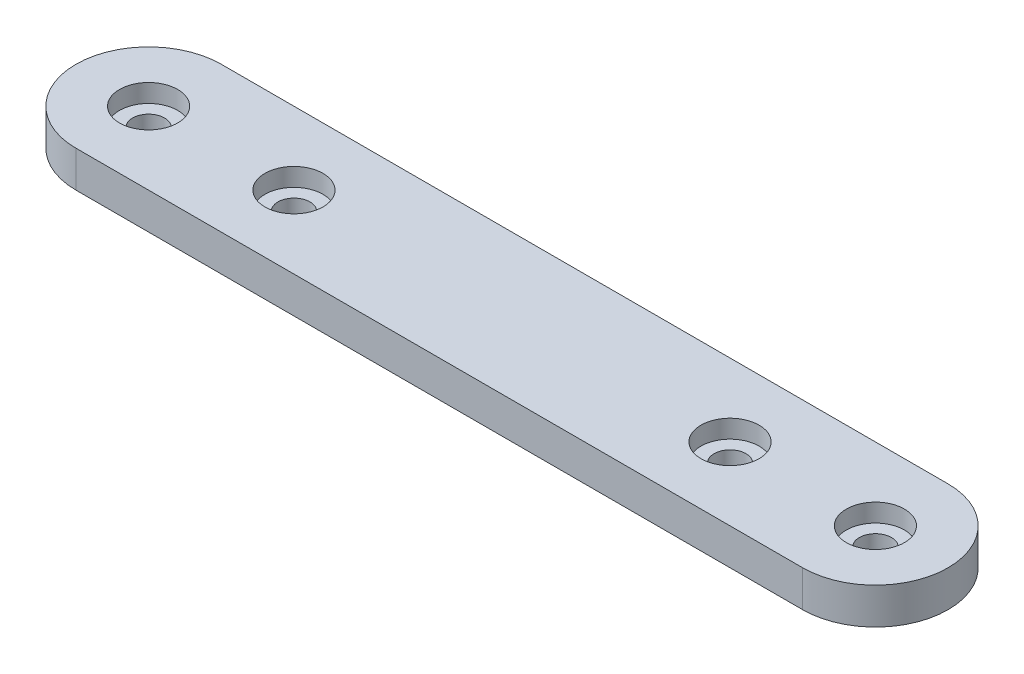
SolidWorks part; units mm, degrees
ref_plane "Front" through (0, 0, 0) normal (0, 0, 1) x (1, 0, 0)
ref_plane "Top" through (0, 0, 0) normal (0, 1, 0) x (1, 0, 0)
ref_plane "Right" through (0, 0, 0) normal (1, 0, 0) x (0, 0, -1)
sketch "Sketch1" plane through (0, 0, 0) normal (0, 1, 0) x (1, 0, 0)
  line L0 (0, 0) -> (127, 0) construction
  line L1 (0, 12.7) -> (127, 12.7)
  line L2 (0, -12.7) -> (127, -12.7)
  arc A0 (0, 12.7) -> (0, -12.7) centre (0, 0) ccw
  arc A1 (127, -12.7) -> (127, 12.7) centre (127, 0) ccw
  circle A2 centre (0, 0) radius 2.794
  circle A3 centre (127, 0) radius 2.8135
  point P3 (63.5, 0)
  dimension "D1" = 5.588
  dimension "D2" = 5.627
  dimension "D3" = 127
  dimension "D4" = 25.4
extrude "Boss-Extrude1" add sketch "Sketch1" along normal blind 6.35
sketch "Sketch3" plane through (0, 6.35, 0) normal (0, 1, 0) x (1, 0, 0)
  circle A0 centre (25.4, 0) radius 2.794
  circle A1 centre (101.6, 0) radius 2.794
  dimension "D1" = 25.4
  dimension "D2" = 76.2
extrude "Cut-Extrude2" cut sketch "Sketch3" against normal up to surface (6.35 mm away) up to face at (63.5, 0, 0)
sketch "Sketch2" plane through (0, 6.35, 0) normal (0, 1, 0) x (1, 0, 0)
  circle A0 centre (0, 0) radius 5.08
  circle A1 centre (127, 0) radius 5.08
  circle A2 centre (25.4, 0) radius 5.08
  circle A3 centre (101.6, 0) radius 5.08
extrude "Cut-Extrude1" cut sketch "Sketch2" against normal blind 3.175
